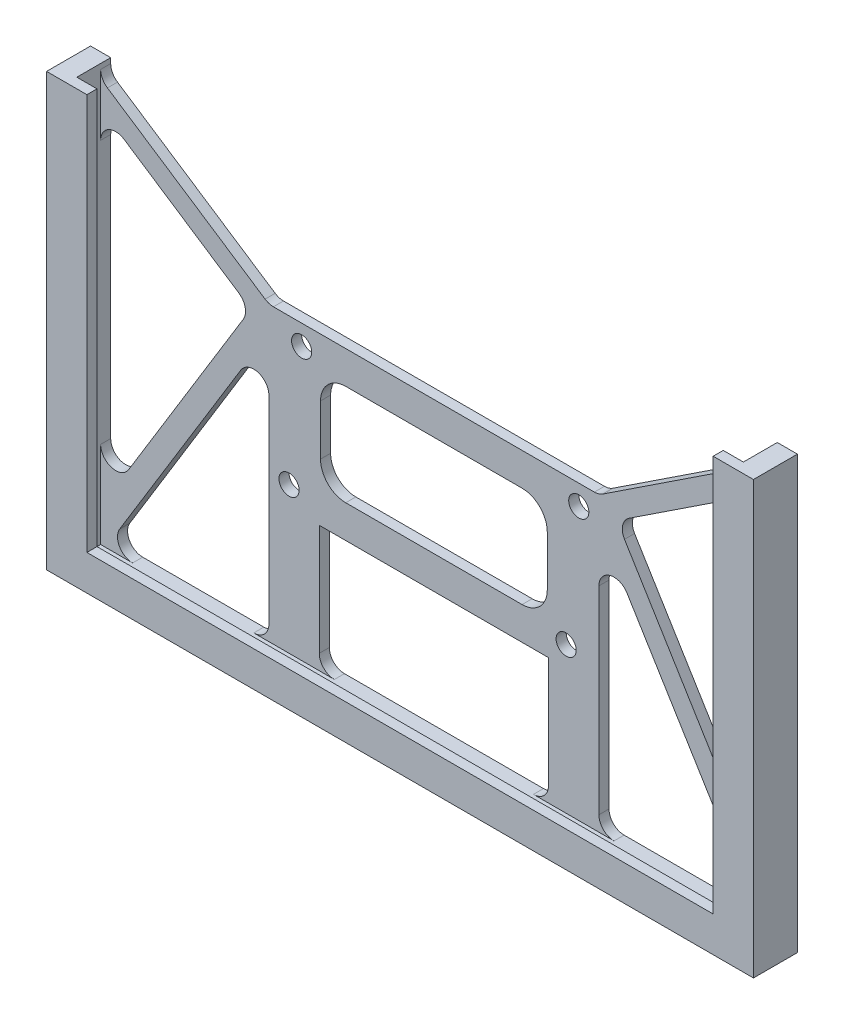
SolidWorks part; units mm, degrees
ref_plane "Front Plane" through (0, 0, 0) normal (0, 0, 1) x (1, 0, 0)
ref_plane "Top Plane" through (0, 0, 0) normal (0, 1, 0) x (1, 0, 0)
ref_plane "Right Plane" through (0, 0, 0) normal (1, 0, 0) x (0, 0, -1)
sketch "Sketch1" plane through (0, 0, 0) normal (0, 0, 1) x (1, 0, 0)
  line L1 (-8.255, 5.08) -> (74.93, 5.08)
  line L2 (-8.255, 5.08) -> (-8.255, -36.83)
  line L3 (-8.255, -36.83) -> (74.93, -36.83)
  line L4 (74.93, 5.08) -> (74.93, -36.83)
  line L5 (4.7625, -3.175) -> (61.9125, -3.175)
  line L6 (4.7625, -3.175) -> (4.7625, -28.575)
  line L7 (4.7625, -28.575) -> (61.9125, -28.575)
  line L8 (61.9125, -3.175) -> (61.9125, -28.575)
  circle A0 centre (0, 0) radius 2.54
  circle A1 centre (-3.175, -31.75) radius 2.54
  circle A2 centre (69.85, 0) radius 2.54
  circle A3 centre (66.675, -31.75) radius 2.54
  point P17 (33.3375, -3.175)
  point P18 (33.3375, 5.08)
  point P19 (4.7625, -15.875)
  point P20 (-8.255, -15.875)
  dimension "D1" = 5.08
  dimension "D2" = 3.175
  dimension "D3" = 3.175
  dimension "D4" = 69.85
  dimension "D5" = 31.75
  dimension "D6" = 5.08
  dimension "D7" = 5.08
  dimension "D8" = 5.08
  dimension "D9" = 5.08
  dimension "D10" = 57.15
  dimension "D11" = 25.4
extrude "Rover mount" add sketch "Sketch1" along normal blind 2.54 contours L4 L1 L2 L3 A3 A2 A1 A0 L5 L8 L7 L6
sketch "Sketch2" plane through (0, 0, 2.54) normal (0, 0, 1) x (1, 0, 0)
  line L1 (-50.6625, -68.58) -> (-8.255, -68.58)
  line L3 (-55.7425, -72.39) -> (122.4175, -72.39)
  line L5 (-8.255, 5.08) -> (74.93, 5.08) construction
  line L6 (-50.6625, -68.58) -> (-50.6625, 36.42)
  line L7 (-50.6625, 36.42) -> (-55.7425, 36.42)
  line L8 (-55.7425, 36.42) -> (-55.7425, -72.39)
  line L11 (122.4175, -72.39) -> (122.4175, 36.42)
  line L12 (122.4175, 36.42) -> (117.3375, 36.42)
  line L13 (117.3375, 36.42) -> (117.3375, -68.58)
  line L14 (-8.255, -36.83) -> (-8.255, -68.58)
  line L15 (-8.255, -36.83) -> (4.445, -36.83)
  line L16 (-8.255, -36.83) -> (74.93, -36.83) construction
  line L17 (4.445, -36.83) -> (4.445, -68.58)
  line L18 (74.93, -36.83) -> (62.23, -36.83)
  line L19 (62.23, -36.83) -> (62.23, -68.58)
  line L20 (74.93, -36.83) -> (74.93, -68.58)
  line L21 (4.445, -68.58) -> (62.23, -68.58)
  line L22 (74.93, -68.58) -> (117.3375, -68.58)
  point P5 (33.3375, -54.7817)
  point P6 (33.3375, 5.08)
  dimension "D1" = 105
  dimension "D2" = 168
  dimension "D3" = 5.08
  dimension "D4" = 3.81
  dimension "D5" = 12.7
  dimension "D6" = 31.75
extrude "Side Walls" add sketch "Sketch2" against normal up to surface and the other way blind 6 up to face at (69.215, -31.75, 0)
sketch "Sketch3" plane through (0, 0, 2.54) normal (0, 0, 1) x (1, 0, 0)
  line L0 (-12.7799, 1.7163) -> (-55.7425, -68.58)
  line L1 (-55.7425, -68.58) -> (-49.3925, -68.58)
  line L2 (-8.255, -68.58) -> (-50.6625, -68.58) construction
  line L3 (-49.3925, -68.58) -> (-8.255, -1.27)
  line L4 (-8.255, 5.08) -> (-8.255, -36.83) construction
  line L5 (-8.255, -1.27) -> (-8.255, 5.08)
  line L6 (79.4549, 1.7163) -> (122.4175, -68.58)
  line L7 (122.4175, -68.58) -> (116.0675, -68.58)
  line L8 (116.0675, -68.58) -> (74.93, -1.27)
  line L9 (74.93, 5.08) -> (74.93, -36.83) construction
  line L10 (74.93, -1.27) -> (74.93, 5.08)
  line L11 (-55.7425, 36.42) -> (-55.7425, -72.39) construction
  line L12 (122.4175, -72.39) -> (122.4175, 36.42) construction
  line L13 (-55.7425, 36.42) -> (-8.255, 5.08)
  line L14 (-12.7799, 1.7163) -> (-55.7425, 30.07)
  line L15 (-55.7425, 30.07) -> (-55.7425, 36.42)
  line L16 (74.93, 5.08) -> (122.4175, 36.42)
  line L17 (122.4175, 36.42) -> (122.4175, 30.07)
  line L18 (122.4175, 30.07) -> (79.4549, 1.7163)
  dimension "D1" = 6.35
extrude "Back Braces" add sketch "Sketch3" against normal blind 2.54
sketch "Sketch4" plane through (0, 0, 8.54) normal (0, 0, 1) x (1, 0, 0)
  line L0 (-55.7425, 36.42) -> (-45.5825, 36.42)
  line L1 (-45.5825, 36.42) -> (-45.5825, -63.5)
  line L2 (-45.5825, -63.5) -> (112.2575, -63.5)
  line L3 (112.2575, -63.5) -> (112.2575, 36.42)
  line L4 (112.2575, 36.42) -> (122.4175, 36.42)
  line L5 (122.4175, 36.42) -> (122.4175, -72.39)
  line L6 (122.4175, -72.39) -> (-55.7425, -72.39)
  line L7 (-55.7425, -72.39) -> (-55.7425, 36.42)
  line L8 (-50.6625, -68.58) -> (-50.6625, 36.42) construction
  line L9 (-8.255, -68.58) -> (-50.6625, -68.58) construction
  dimension "D1" = 5.08
  dimension "D2" = 5.08
extrude "Front Cover" add sketch "Sketch4" along normal blind 2.54
sketch "Sketch5" plane through (0, -36.83, 0) normal (0, 1, 0) x (1, 0, 0)
  line L0 (74.93, -2.54) -> (74.93, 0) construction
  line L1 (-8.255, -8.54) -> (74.93, -8.54)
  line L2 (-8.255, -8.54) -> (-8.255, -2.54)
  line L3 (-8.255, -2.54) -> (74.93, -2.54)
  line L4 (74.93, -8.54) -> (74.93, -2.54)
  line L5 (117.3375, -2.54) -> (74.93, -2.54) construction
extrude "Cleanup" cut sketch "Sketch5" against normal up to surface (31.75 mm away) up to face at (-36.1033, -68.58, 3.6933)
fillet "Fillet1" radius 3.81 18 edges at (62.23, -68.58, 1.27) (4.445, -68.58, 1.27) (117.3375, -60.268, 1.27) (116.0675, -68.58, 1.27) (74.93, -68.58, 1.27) (74.93, -1.27, 1.27) (-8.255, -1.27, 1.27) (-8.255, -68.58, 1.27) (-49.3925, -68.58, 1.27) (-50.6625, -60.268, 1.27) (117.3375, 26.7174, 1.27) (117.3375, 33.0674, 1.27) (79.4549, 1.7163, 1.27) (-12.7799, 1.7163, 1.27) (-50.6625, 26.7174, 1.27) (-50.6625, 33.0674, 1.27) (74.93, 5.08, 1.27) (-8.255, 5.08, 1.27)
fillet "Fillet2" radius 6.35 4 edges at (4.7625, -3.175, 1.27) (4.7625, -28.575, 1.27) (61.9125, -3.175, 1.27) (61.9125, -28.575, 1.27)
